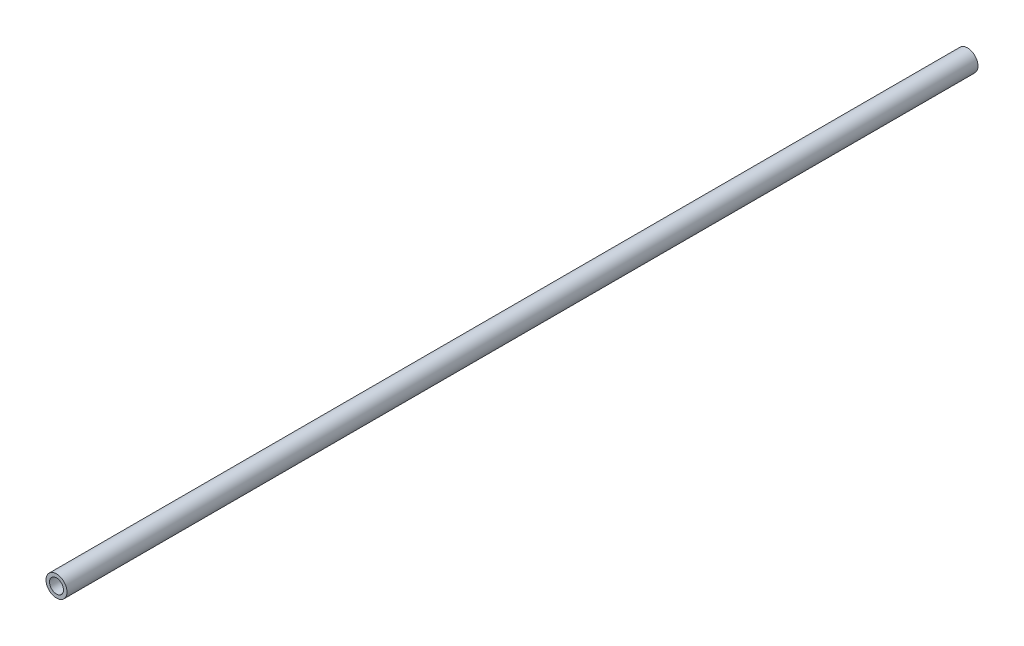
SolidWorks part; units mm, degrees
material "Poltrusion Carbon Fiber"
ref_plane "Front Plane" through (0, 0, 0) normal (0, 0, 1) x (1, 0, 0)
ref_plane "Top Plane" through (0, 0, 0) normal (0, 1, 0) x (1, 0, 0)
ref_plane "Right Plane" through (0, 0, 0) normal (1, 0, 0) x (0, 0, -1)
sketch "Sketch1" plane through (0, 0, 0) normal (0, 0, 1) x (1, 0, 0)
  circle A0 centre (0, 0) radius 3
  circle A2 centre (0, 0) radius 2
  dimension "D1" = 6
  dimension "D2" = 1
extrude "Boss-Extrude1" add sketch "Sketch1" along normal mid plane 260
equation "\"DTailTube\"= 16mm'Диаметр трубки хвостового оперения"
equation "\"FusLenght\"= 700mm"
equation "\"DMotor\"= 35.2mm"
equation "\"MotorArm\"= 320mm"
equation "\"DFus\"= 150mm"
equation "\"DFusTube\"= 30mm'Диаметр трубки внутри фюзеляжа"
equation "\"FusTubeHeight\"= 40mm"
equation "\"FusCentralPartLenght\"= 410mm"
equation "\"FusNoseLenght\"= 150mm"
equation "\"WingOffset\"= 1mm'Расстояние от внутренней поверхности фюзеляжа до профиля крыла по вертикали"
equation "\"EllipseRatio\"= 0.95'Центральная часть фюзеляжа - эллипс. Этот параметр - отношение длин осей эллипса"
equation "\"FrameOffset\"= 0.6mm"
equation "\"DThreadedInsert\"= 3mm'Внешний диамер резьбовых втулок"
equation "\"ThreadedInsertLenght\"=4mm'Длина резьбовых втулок"
equation "\"ThreadedInsertThread\"=2mm'Диаметр резьбы втулки"
equation "\"CenterSectionLenght\"= 140mm'Длина центроплана"
equation "\"b\"= 1700mm'Размах"
equation "\"cwr\"= 236mm'Корневая хорда крыла"
equation "\"TR\"= 0.75'Сужение крыла"
equation "\"cwt\"= \"TR\" * \"cwr\"'Концевая хорда крыла"
equation "\"DWingMainSpar\"= 16mm'Диаметр главного лонжерона крыла"
equation "\"DWingSecondSpar\"= 8mm'Диаметр второго лонжерона крыла"
equation "\"WingSparsDistance\"= 80mm'Расстояния между отверстиями по лонжерон крыла"
equation "\"c\"= 210mm'САХ крыла"
equation "\"FusTubeLenght\"= \"FusLenght\"-90mm'Длина трубки фюзеляжа"
equation "\"bt\"=291mm'Высота лопатки хвоста"
equation "\"ct\"=182mm'Корневая хорда хвоста"
equation "\"lambda_t\"=0.3'Доля хвоста, занатая рулем высоты"
equation "\"TailTubeLenght\"=680mm'Длина хвостовой балки"
equation "\"DStringer\"=6mm'Диаметр стрингеров"
equation "\"TailConnectorBaseLenght\"=20mm'Высота основания конектора хвоста"
equation "\"CargoHolderHoleDistance\"=30mm'Расстояние между крепежными отверстиями для держателя груза"
equation "\"FuselageThickness\"=1.2mm'Толщина фюзеляжа"
equation "\"DTailSpar\"=6mm'Диаметр лонжерона хвостового оперения"
equation "\"TailSparDistance\"=40mm'Расстояние между лонжеронами хвостового оперения"
equation "\"CrossSectionWidth\"=15mm'Ширина кольцевой части шпангоута"
equation "\"HingeLenght\"=30mm'Длина отверстия под шарнир хвостового оперения"
equation "\"HingeWidth\"=2.4mm'Высота отверстия под шарнир ХО"
equation "\"HingeDepth\"=15mm'Глубина отверстия под шарнир ХО"
equation "\"D1@Sketch1\"=\"DTailSpar\""
